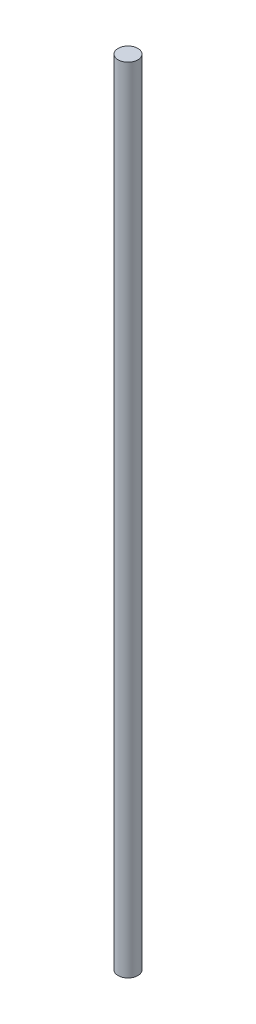
SolidWorks part; units mm, degrees
ref_plane "前视基准面" through (0, 0, 0) normal (0, 0, 1) x (1, 0, 0)
ref_plane "上视基准面" through (0, 0, 0) normal (0, 1, 0) x (1, 0, 0)
ref_plane "右视基准面" through (0, 0, 0) normal (1, 0, 0) x (0, 0, -1)
sketch "草图1" plane through (0, 0, 0) normal (0, 1, 0) x (1, 0, 0)
  circle A0 centre (0, 0) radius 2.5
  dimension "D1" = 5
extrude "凸台-拉伸1" add sketch "草图1" along normal blind 200
